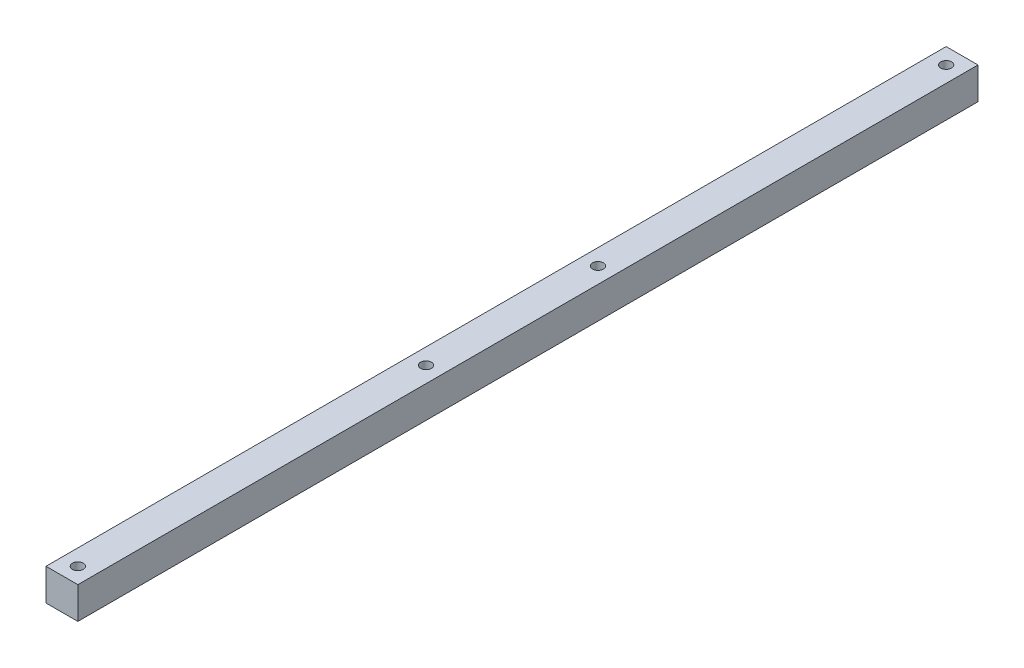
SolidWorks part; units mm, degrees
ref_plane "Front Plane" through (0, 0, 0) normal (0, 0, 1) x (1, 0, 0)
ref_plane "Top Plane" through (0, 0, 0) normal (0, 1, 0) x (1, 0, 0)
ref_plane "Right Plane" through (0, 0, 0) normal (1, 0, 0) x (0, 0, -1)
sketch "Sketch1" plane through (0, 0, 0) normal (0, 0, 1) x (1, 0, 0)
  line L1 (-2.5, -2.5) -> (2.5, -2.5)
  line L2 (-2.5, -2.5) -> (-2.5, 2.5)
  line L3 (-2.5, 2.5) -> (2.5, 2.5)
  line L4 (2.5, -2.5) -> (2.5, 2.5)
  line L5 (-2.5, -2.5) -> (2.5, 2.5) construction
  line L6 (-2.5, 2.5) -> (2.5, -2.5) construction
  point P0 (0, 0)
  dimension "D1" = 5
  dimension "D2" = 5
extrude "Boss-Extrude1" add sketch "Sketch1" along normal blind 141.3
sketch "Sketch3" plane through (0, -2.5, 0) normal (0, -1, 0) x (1, 0, 0)
  line L0 (0, 141.3) -> (0, 0) construction
  line L1 (-2.5, 141.3) -> (2.5, 141.3) construction
  line L2 (-2.5, 0) -> (2.5, 0) construction
  line L3 (2.5, 70.65) -> (-2.5, 70.65) construction
  line L4 (2.5, 141.3) -> (2.5, 0) construction
  line L5 (-2.5, 141.3) -> (-2.5, 0) construction
  circle A0 centre (0, 138.8) radius 0.85
  circle A1 centre (0, 2.5) radius 0.85
  circle A2 centre (0, 84.15) radius 0.85
  circle A3 centre (0, 57.15) radius 0.85
  dimension "D1" = 1.7
  dimension "D2" = 2.5
  dimension "D3" = 1.7
  dimension "D4" = 54.65
extrude "Cut-Extrude2" cut sketch "Sketch3" against normal through all
